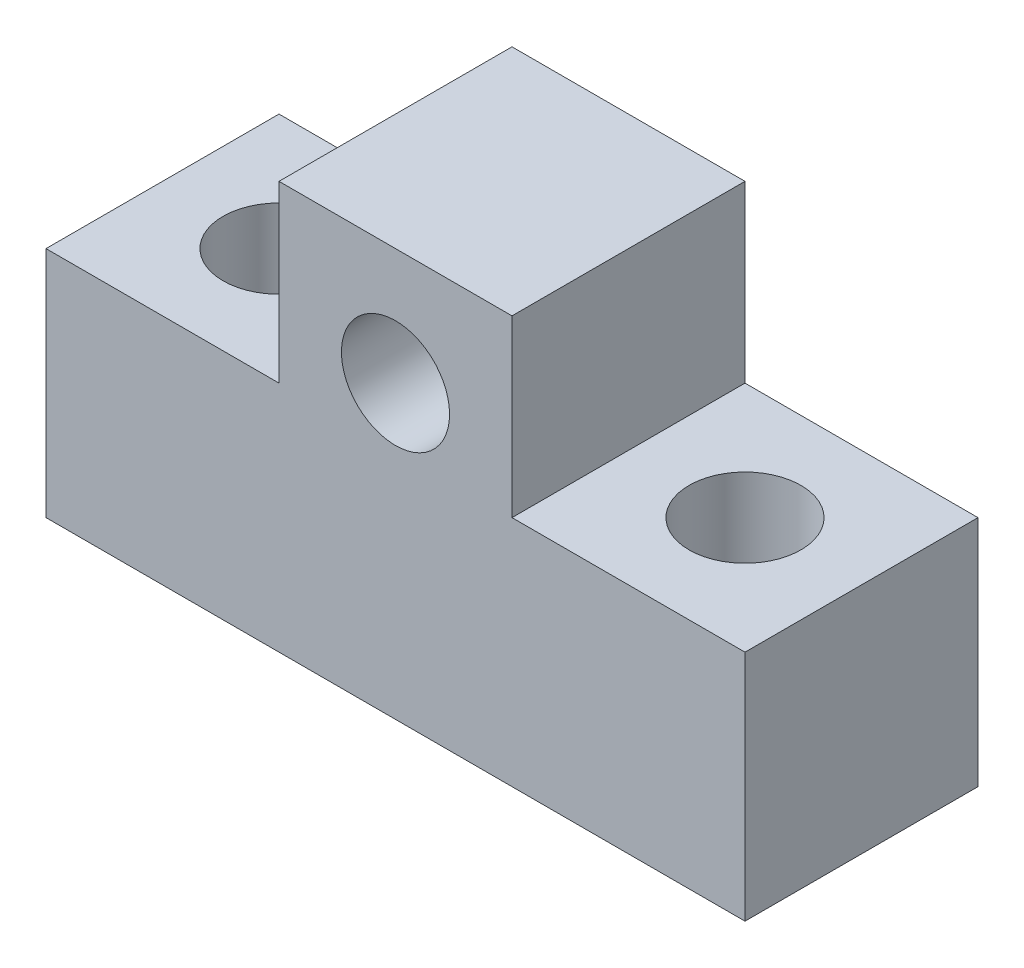
SolidWorks part; units mm, degrees
ref_plane "Front Plane" through (0, 0, 0) normal (0, 0, 1) x (1, 0, 0)
ref_plane "Top Plane" through (0, 0, 0) normal (0, 1, 0) x (1, 0, 0)
ref_plane "Right Plane" through (0, 0, 0) normal (1, 0, 0) x (0, 0, -1)
sketch "Sketch1" plane through (0, 0, 0) normal (0, 0, 1) x (1, 0, 0)
  line L0 (-9.525, 3.175) -> (9.525, -3.175) construction
  line L1 (-9.525, 3.175) -> (9.525, 3.175)
  line L2 (-9.525, 3.175) -> (-9.525, -3.175)
  line L3 (-9.525, -3.175) -> (9.525, -3.175)
  line L4 (9.525, 3.175) -> (9.525, -3.175)
  point P4 (0, 0)
  dimension "D1" = 19.05
  dimension "D2" = 6.35
extrude "Boss-Extrude1" add sketch "Sketch1" along normal blind 6.35
sketch "Sketch6" plane through (0, 3.175, 0) normal (0, 1, 0) x (1, 0, 0)
  line L0 (9.525, 0) -> (-9.525, 0) construction
  line L1 (3.175, 0) -> (-3.175, 0)
  line L2 (3.175, 0) -> (3.175, -6.35)
  line L3 (3.175, -6.35) -> (-3.175, -6.35)
  line L4 (-3.175, 0) -> (-3.175, -6.35)
  line L5 (9.525, -6.35) -> (-9.525, -6.35) construction
  point P8 (0, 0)
  point P9 (0, 0)
  dimension "D1" = 6.35
extrude "Boss-Extrude2" add sketch "Sketch6" along normal blind 4.7625
hole_wizard "Tapped Hole for #4-40 Helicoil1" positions "Sketch2" profile "Sketch3" tap size "#4-40" standard "Helicoil® Inch" end condition through all
sketch "Sketch2" plane through (0, 3.175, 0) normal (0, 1, 0) x (1, 0, 0)
  line L0 (0, 0) -> (0, -6.35) construction
  line L4 (-9.525, -6.35) -> (-9.525, 0) construction
  line L5 (-9.525, -6.35) -> (9.525, -6.35) construction
  line L6 (-9.525, 0) -> (9.525, 0) construction
  point P0 (-6.35, -3.175)
  point P13 (6.35, -3.175)
  point P16 (0, -3.175)
  dimension "D1" = 3.175
sketch "Sketch3" plane through (-6.35, 3.175, 3.175) normal (1, 0, 0) x (0, 0, 1)
  line L0 (0, 0) -> (0, 6.35)
  line L1 (0, 6.35) -> (1.524, 6.35)
  line L2 (1.524, 6.35) -> (1.524, 0)
  line L5 (1.524, 0) -> (0, 0)
  line L11 (0, -6.35) -> (0, 107.95) construction
  dimension "Thru Tap Drill Dia." = 3.048
  dimension "Thru Tap Drill Depth" = 6.35
cosmetic thread "Hole Thread1" parameters "D1"=3.556, "D2"=3.7414
cosmetic thread "Hole Thread2" parameters "D1"=3.556, "D2"=3.7414
hole_wizard "#4 Clearance Hole2" positions "Sketch4" profile "Sketch5" hole size "#4" standard "ANSI Inch" end condition through all
sketch "Sketch4" plane through (0, 0, 6.35) normal (0, 0, 1) x (1, 0, 0)
  line L6 (-3.175, 4.7625) -> (0, 4.7625) construction
  line L7 (-3.175, 7.9375) -> (-3.175, 3.175) construction
  line L8 (0, 4.7625) -> (0, 7.9375) construction
  line L9 (-3.175, 7.9375) -> (3.175, 7.9375) construction
  point P0 (0, 4.7625)
sketch "Sketch5" plane through (0, 4.7625, 6.35) normal (1, 0, 0) x (0, -1, 0)
  line L0 (0, 0) -> (0, 6.35)
  line L1 (0, 6.35) -> (1.4732, 6.35)
  line L2 (1.4732, 6.35) -> (1.4732, 0)
  line L5 (1.4732, 0) -> (0, 0)
  line L11 (0, -6.35) -> (0, 107.95) construction
  dimension "Thru Hole Dia." = 2.9464
  dimension "Thru Hole Depth" = 6.35
